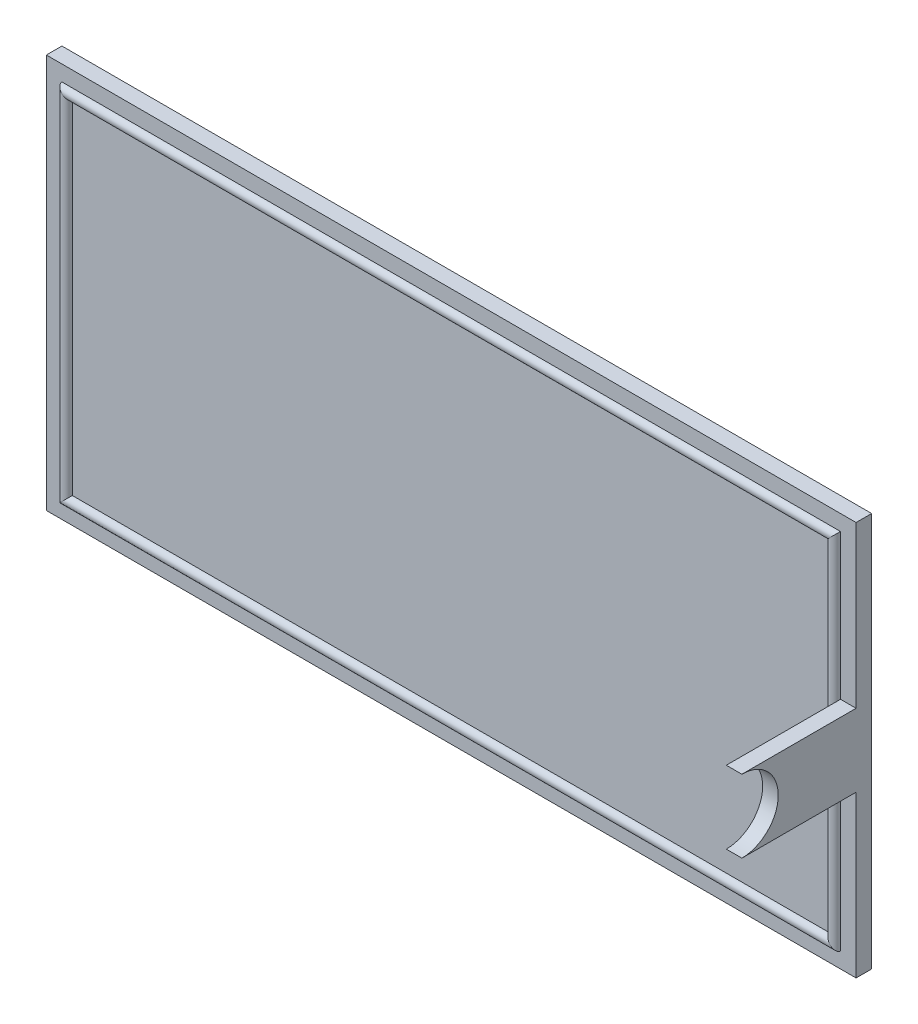
SolidWorks part; units mm, degrees
ref_plane "Plan de face" through (0, 0, 0) normal (0, 0, 1) x (1, 0, 0)
ref_plane "Plan de dessus" through (0, 0, 0) normal (0, 1, 0) x (1, 0, 0)
ref_plane "Plan de droite" through (0, 0, 0) normal (1, 0, 0) x (0, 0, -1)
sketch "Esquisse1" plane through (0, 0, 0) normal (0, 0, 1) x (1, 0, 0)
  line L1 (0, 0) -> (78, 0)
  line L2 (0, 0) -> (0, 38)
  line L3 (0, 38) -> (78, 38)
  line L4 (78, 0) -> (78, 38)
  dimension "D1" = 78
  dimension "D2" = 38
extrude "Boss.-Extru.1" add sketch "Esquisse1" along normal blind 1.5
sketch3d "Esquisse3D1"
  line L0 (2, 2, 1.5) -> (76, 2, 1.5)
  line L1 (76, 2, 1.5) -> (76, 36, 1.5)
  line L2 (76, 36, 1.5) -> (2, 36, 1.5)
  line L3 (2, 36, 1.5) -> (2, 2, 1.5)
  line L8 (2, 2, 1.5) -> (76, 2, 1.5)
  line L9 (76, 2, 1.5) -> (76, 36, 1.5)
  line L10 (76, 36, 1.5) -> (2, 36, 1.5)
  line L11 (2, 36, 1.5) -> (2, 2, 1.5)
  dimension "D1" = 2
sweep "Balayage1" add path "Esquisse3D1" circular profile diameter 1 parameters "D3"=1
sketch "Esquisse14" plane through (0, 0, 1.5) normal (0, 0, 1) x (1, 0, 0)
  line L0 (76.5, 36.5) -> (76.5, 1.5) construction
  line L1 (76.5, 22.5) -> (78, 22.5)
  line L2 (76.5, 22.5) -> (76.5, 15.5)
  line L3 (76.5, 15.5) -> (78, 15.5)
  line L4 (78, 22.5) -> (78, 15.5)
  line L5 (78, 0) -> (78, 38) construction
  point P8 (78, 19)
  dimension "D1" = 7
extrude "Boss.-Extru.2" add sketch "Esquisse14" along normal blind 11
sketch "Esquisse15" plane through (78, 0, 0) normal (1, 0, 0) x (0, 0, -1)
  line L0 (-12.5, 19) -> (-14.3769, 19) construction
  line L1 (-12.5, 15.5) -> (-12.5, 22.5) construction
  line L2 (-12.5, 15.5) -> (-14.3769, 15.5)
  line L3 (-12.5, 22.5) -> (-14.3769, 22.5)
  arc A0 (-12.5, 15.5) -> (-12.5, 22.5) centre (-12.5, 19) ccw
  arc A1 (-14.3769, 22.5) -> (-14.3769, 15.5) centre (-14.3769, 19) ccw
  point P4 (-13.4384, 19)
  point P11 (-14.3769, 19)
  dimension "D1" = 3.5
extrude "Enlèv. mat.-Extru.1" cut sketch "Esquisse15" against normal blind 11
